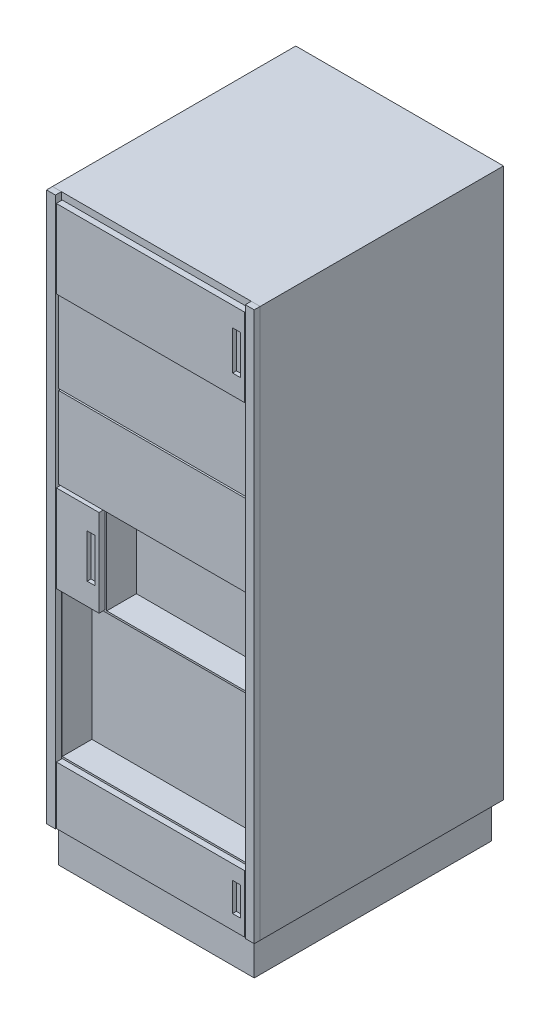
SolidWorks part; units mm, degrees
ref_plane "Front Plane" through (0, 0, 0) normal (0, 0, 1) x (1, 0, 0)
ref_plane "Top Plane" through (0, 0, 0) normal (0, 1, 0) x (1, 0, 0)
ref_plane "Right Plane" through (0, 0, 0) normal (1, 0, 0) x (0, 0, -1)
other "Configuration Table"
sketch "Sketch1" plane through (0, 0, 0) normal (0, 0, 1) x (1, 0, 0)
  line L1 (0, 120) -> (700, 120)
  line L2 (0, 120) -> (0, 1970)
  line L3 (0, 1970) -> (700, 1970)
  line L4 (700, 120) -> (700, 1970)
extrude "govde_kasa" add sketch "Sketch1" against normal blind 820 separate body
sketch "Sketch2" plane through (0, 0, 0) normal (0, 0, 1) x (1, 0, 0)
  line L1 (20, 0) -> (680, 0)
  line L2 (20, 0) -> (20, 120)
  line L3 (20, 120) -> (680, 120)
  line L4 (680, 0) -> (680, 120)
extrude "plint" add sketch "Sketch2" against normal blind 800 separate body
sketch "Sketch3" plane through (0, 0, 0) normal (0, 0, 1) x (1, 0, 0)
  line L1 (0, 120) -> (30, 120)
  line L2 (0, 120) -> (0, 1970)
  line L3 (0, 1970) -> (30, 1970)
  line L4 (30, 120) -> (30, 1970)
extrude "sove_sol" add sketch "Sketch3" along normal blind 20 separate body
sketch "Sketch4" plane through (0, 0, 0) normal (0, 0, 1) x (1, 0, 0)
  line L1 (670, 120) -> (700, 120)
  line L2 (670, 120) -> (670, 1970)
  line L3 (670, 1970) -> (700, 1970)
  line L4 (700, 120) -> (700, 1970)
extrude "sove_sag" add sketch "Sketch4" along normal blind 20 separate body
sketch "Sketch5" plane through (0, 0, 0) normal (0, 0, 1) x (1, 0, 0)
  line L1 (33, 1683) -> (667, 1683)
  line L2 (33, 1683) -> (33, 1947)
  line L3 (33, 1947) -> (667, 1947)
  line L4 (667, 1683) -> (667, 1947)
extrude "kapak_fan_filtre" add sketch "Sketch5" along normal blind 20 separate body
sketch "Sketch6" plane through (0, 0, 0) normal (0, 0, 1) x (1, 0, 0)
  line L1 (627, 1749) -> (653, 1749)
  line L2 (627, 1749) -> (627, 1881)
  line L3 (627, 1881) -> (653, 1881)
  line L4 (653, 1749) -> (653, 1881)
extrude "kapak_fan_filtre_kulp" cut sketch "Sketch6" along normal blind 13 from offset 7
sketch "Sketch7" plane through (0, 0, 0) normal (0, 0, 1) x (1, 0, 0)
  line L1 (33, 1403) -> (667, 1403)
  line L2 (33, 1403) -> (33, 1677)
  line L3 (33, 1677) -> (667, 1677)
  line L4 (667, 1403) -> (667, 1677)
extrude "firin_kapak_2_cam" add sketch "Sketch7" along normal blind 12 separate body
sketch "Sketch8" plane through (0, 0, 0) normal (0, 0, 1) x (1, 0, 0)
  line L1 (33, 1123) -> (667, 1123)
  line L2 (33, 1123) -> (33, 1397)
  line L3 (33, 1397) -> (667, 1397)
  line L4 (667, 1123) -> (667, 1397)
extrude "firin_kapak_1_cam" add sketch "Sketch8" along normal blind 12 separate body
sketch "Sketch9" plane through (0, 0, 0) normal (0, 0, 1) x (1, 0, 0)
  line L1 (33, 823) -> (177, 823)
  line L2 (33, 823) -> (33, 1117)
  line L3 (33, 1117) -> (177, 1117)
  line L4 (177, 823) -> (177, 1117)
extrude "kapak_yag_kabi" add sketch "Sketch9" along normal blind 20 separate body
sketch "Sketch10" plane through (0, 0, 0) normal (0, 0, 1) x (1, 0, 0)
  line L1 (137, 896.5) -> (163, 896.5)
  line L2 (137, 896.5) -> (137, 1043.5)
  line L3 (137, 1043.5) -> (163, 1043.5)
  line L4 (163, 896.5) -> (163, 1043.5)
extrude "kapak_yag_kabi_kulp" cut sketch "Sketch10" along normal blind 13 from offset 7
sketch "Sketch11" plane through (0, 0, 0) normal (0, 0, 1) x (1, 0, 0)
  line L1 (183, 823) -> (667, 823)
  line L2 (183, 823) -> (183, 1117)
  line L3 (183, 1117) -> (667, 1117)
  line L4 (667, 823) -> (667, 1117)
extrude "aciklik_sprey" cut sketch "Sketch11" against normal blind 100
sketch "Sketch12" plane through (0, 0, 0) normal (0, 0, 1) x (1, 0, 0)
  line L1 (33, 323) -> (667, 323)
  line L2 (33, 323) -> (33, 817)
  line L3 (33, 817) -> (667, 817)
  line L4 (667, 323) -> (667, 817)
extrude "aciklik_kesme" cut sketch "Sketch12" against normal blind 100
sketch "Sketch13" plane through (0, 0, 0) normal (0, 0, 1) x (1, 0, 0)
  line L1 (33, 123) -> (667, 123)
  line L2 (33, 123) -> (33, 317)
  line L3 (33, 317) -> (667, 317)
  line L4 (667, 123) -> (667, 317)
extrude "kapak_pano" add sketch "Sketch13" along normal blind 20 separate body
sketch "Sketch14" plane through (0, 0, 0) normal (0, 0, 1) x (1, 0, 0)
  line L1 (627, 171.5) -> (653, 171.5)
  line L2 (627, 171.5) -> (627, 268.5)
  line L3 (627, 268.5) -> (653, 268.5)
  line L4 (653, 171.5) -> (653, 268.5)
extrude "kapak_pano_kulp" cut sketch "Sketch14" along normal blind 13 from offset 7
